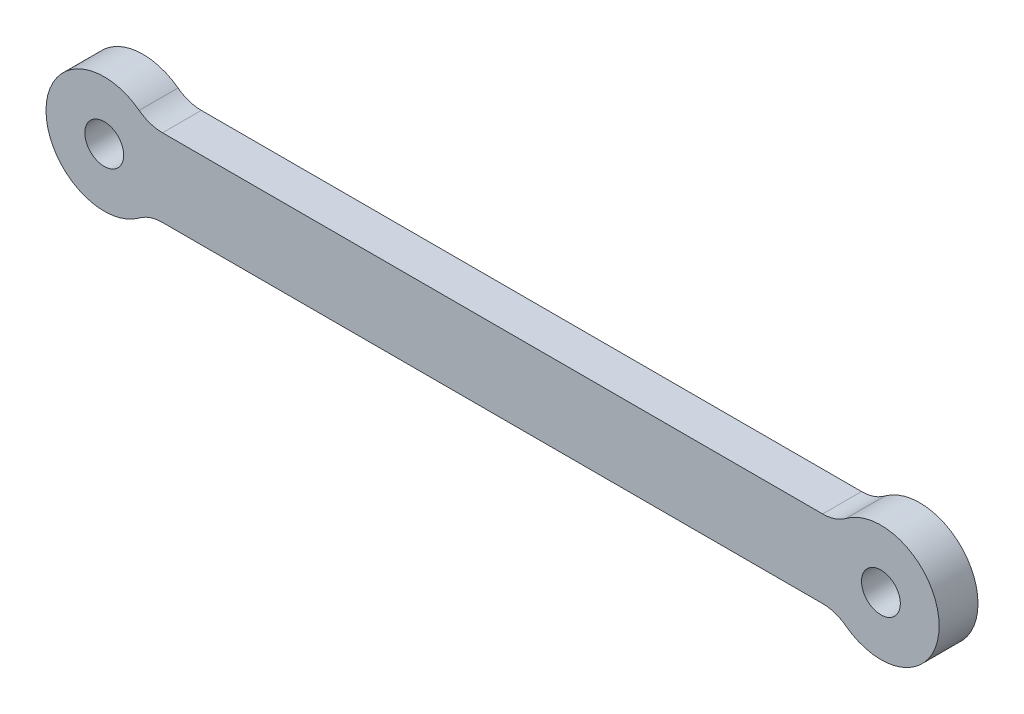
SolidWorks part; units mm, degrees
ref_plane "Front Plane" through (0, 0, 0) normal (0, 0, 1) x (1, 0, 0)
ref_plane "Top Plane" through (0, 0, 0) normal (0, 1, 0) x (1, 0, 0)
ref_plane "Right Plane" through (0, 0, 0) normal (1, 0, 0) x (0, 0, -1)
sketch "Sketch1" plane through (0, 0, 0) normal (0, 0, 1) x (1, 0, 0)
  line L0 (-127, 0) -> (0, 0) construction
  line L1 (-117.475, 6.35) -> (-9.525, 6.35)
  line L2 (-9.525, -6.35) -> (-117.475, -6.35)
  arc A0 (-5.715, -7.62) -> (-5.715, 7.62) centre (0, 0) ccw
  arc A1 (-121.285, 7.62) -> (-121.285, -7.62) centre (-127, 0) ccw
  arc A2 (-117.475, -6.35) -> (-121.285, -7.62) centre (-117.475, -12.7) ccw
  arc A3 (-9.525, -6.35) -> (-5.715, -7.62) centre (-9.525, -12.7) cw
  arc A4 (-9.525, 6.35) -> (-5.715, 7.62) centre (-9.525, 12.7) ccw
  arc A5 (-117.475, 6.35) -> (-121.285, 7.62) centre (-117.475, 12.7) cw
  circle A6 centre (-127, 0) radius 3.175
  circle A7 centre (0, 0) radius 3.175
  dimension "D1" = 19.05
  dimension "D4" = 6.35
  dimension "D5" = 6.35
  dimension "D2" = 127
  dimension "D3" = 12.7
extrude "Boss-Extrude1" add sketch "Sketch1" along normal mid plane 6.35
